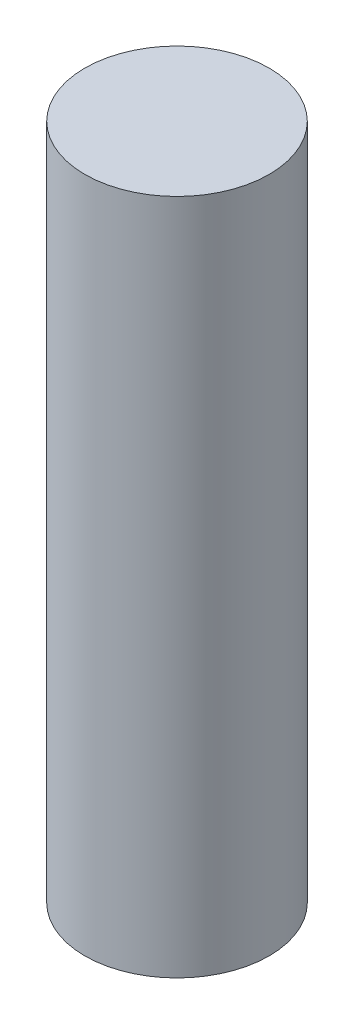
SolidWorks part; units mm, degrees
ref_plane "Front Plane" through (0, 0, 0) normal (0, 0, 1) x (1, 0, 0)
ref_plane "Top Plane" through (0, 0, 0) normal (0, 1, 0) x (1, 0, 0)
ref_plane "Right Plane" through (0, 0, 0) normal (1, 0, 0) x (0, 0, -1)
sketch "Sketch3" plane through (0, 0, 0) normal (0, 1, 0) x (1, 0, 0)
  circle A0 centre (0, 0) radius 9.45
  dimension "D1" = 18.9
extrude "Boss-Extrude1" add sketch "Sketch3" along normal blind 69.41
